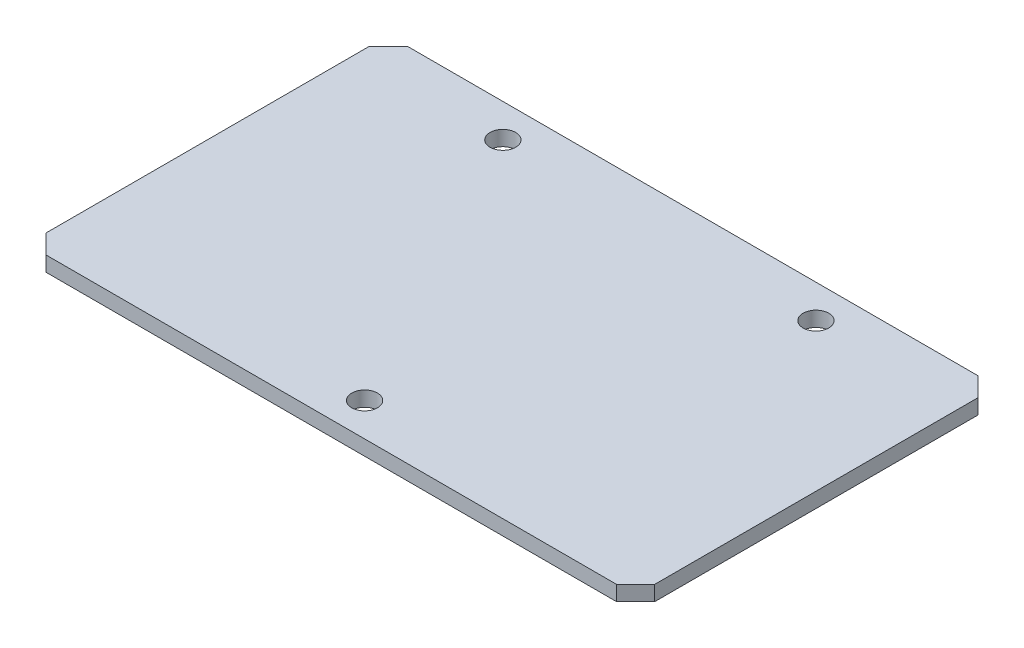
SolidWorks part; units mm, degrees
material "1060 Alloy"
ref_plane "Front Plane" through (0, 0, 0) normal (0, 0, 1) x (1, 0, 0)
ref_plane "Top Plane" through (0, 0, 0) normal (0, 1, 0) x (1, 0, 0)
ref_plane "Right Plane" through (0, 0, 0) normal (1, 0, 0) x (0, 0, -1)
sketch "Sketch1" plane through (0, 0, 0) normal (0, 1, 0) x (1, 0, 0)
  line L1 (-32, -19) -> (32, -19)
  line L2 (-32, -19) -> (-32, 19)
  line L3 (-32, 19) -> (32, 19)
  line L4 (32, -19) -> (32, 19)
  line L5 (-32, -19) -> (32, 19) construction
  line L6 (-32, 19) -> (32, -19) construction
  point P0 (0, 0)
  dimension "D1" = 64
  dimension "D2" = 38
extrude "Boss-Extrude1" add sketch "Sketch1" along normal blind 1.5788
chamfer "Chamfer1" distance 2 angle 45 8 edges at (32, 0.7894, 19) (0, 1.5788, 19) (-32, 0.7894, 19) (-32, 1.5788, 0) (-32, 0.7894, -19) (32, 0.7894, -19) (0, 1.5788, -19) (32, 1.5788, 0)
sketch "Sketch3" plane through (0, 1.5788, 0) normal (0, 1, 0) x (1, 0, 0)
  line L0 (0, -19) -> (0, -15.5) construction
  line L1 (-30, -19) -> (30, -19) construction
  line L2 (0, -15.5) -> (-32, -15.5) construction
  line L3 (-32, 17) -> (-32, -17) construction
  line L4 (-32, 15.5) -> (32, 15.5) construction
  line L5 (32, -17) -> (32, 17) construction
  line L6 (30, 19) -> (-30, 19) construction
  line L7 (-16.46, 15.5) -> (-16.46, 19) construction
  line L8 (16.46, 15.5) -> (16.46, 19) construction
  circle A0 centre (-16.46, 15.5) radius 1.35
  circle A1 centre (16.46, 15.5) radius 1.35
  circle A2 centre (0, -15.5) radius 1.35
  dimension "D5" = 2.7
  dimension "D6" = 2.7
  dimension "D7" = 2.7
  dimension "D1" = 3.5
  dimension "D2" = 3.5
  dimension "D3" = 15.54
  dimension "D4" = 15.54
extrude "Cut-Extrude1" cut sketch "Sketch3" against normal through all contours A2 | A0 | A1
